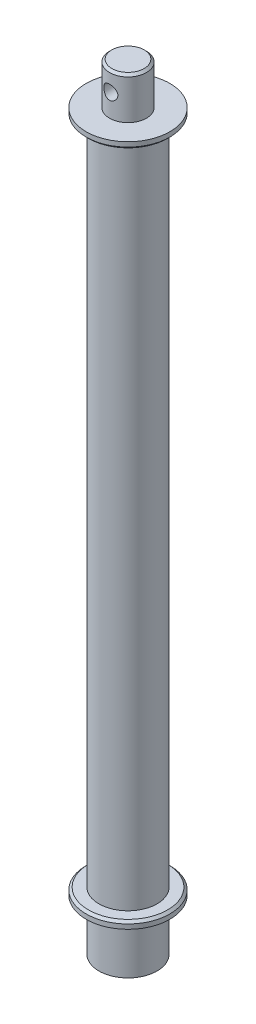
SolidWorks part; units mm, degrees
material "普通碳钢"
ref_plane "前视基准面" through (0, 0, 0) normal (0, 0, 1) x (1, 0, 0)
ref_plane "上视基准面" through (0, 0, 0) normal (0, 1, 0) x (1, 0, 0)
ref_plane "右视基准面" through (0, 0, 0) normal (1, 0, 0) x (0, 0, -1)
sketch "草图1" plane through (0, 0, 0) normal (0, 1, 0) x (1, 0, 0)
  circle A0 centre (0, 0) radius 7.95
  dimension "D1" = 15.9
extrude "凸台-拉伸1" add sketch "草图1" along normal blind 18 contours A0
sketch "草图9" plane through (0, 0, 0) normal (0, 0, 1) x (1, 0, 0)
  line L0 (0, -8.745) -> (0, 8.745) construction
  line L1 (8.745, 0) -> (-8.745, 0) construction
  circle A0 centre (0, 9.7) radius 3
  dimension "D1" = 9.7
  dimension "D2" = 6
extrude "切除-拉伸2" cut sketch "草图9" against normal through all both and the other way through all
chamfer "倒角2" distance 1 angle 45 1 edges at (0, 18, 7.95)
sketch "草图4" plane through (0, 0, 0) normal (0, 1, 0) x (1, 0, 0)
  circle A0 centre (0, 0) radius 18
extrude "凸台-拉伸2" add sketch "草图4" against normal blind 3
chamfer "倒角1" distance 1 angle 45 1 edges at (0, -3, 18)
ref_plane "基准面4" through (0, -3, 0) normal (0, -1, 0) x (-1, 0, 0)
sketch "草图5" plane through (0, -3, 0) normal (0, -1, 0) x (-1, 0, 0)
  circle A0 centre (0, 0) radius 12.5
extrude "凸台-拉伸3" add sketch "草图5" along normal blind 287.21
ref_plane "基准面5" through (0, -290.21, 0) normal (0, -1, 0) x (-1, 0, 0)
sketch "草图11" plane through (0, -290.21, 0) normal (0, -1, 0) x (-1, 0, 0)
  circle A0 centre (0, 0) radius 18
extrude "凸台-拉伸4" add sketch "草图11" along normal blind 3
chamfer "倒角3" distance 1 angle 45 1 edges at (0, -290.21, -18)
ref_plane "基准面6" through (0, -293.21, 0) normal (0, -1, 0) x (-1, 0, 0)
sketch "草图12" plane through (0, -293.21, 0) normal (0, -1, 0) x (-1, 0, 0)
  circle A0 centre (0, 0) radius 12.5
  arc A1 (1.3201, 7.2813) -> (1.0368, 7.327) centre (0, 0) ccw
  arc A2 (-0.3333, 7.3925) -> (-0.6196, 7.374) centre (0, 0) ccw
  arc A3 (-1.9699, 7.133) -> (-2.2449, 7.0513) centre (0, 0) ccw
  arc A4 (-3.5077, 6.5158) -> (-3.7577, 6.3749) centre (0, 0) ccw
  arc A5 (-4.8697, 5.5719) -> (-5.082, 5.3789) centre (0, 0) ccw
  arc A6 (-5.9875, 4.3486) -> (-6.1516, 4.1132) centre (0, 0) ccw
  arc A7 (-6.805, 2.9072) -> (-6.9126, 2.6412) centre (0, 0) ccw
  arc A8 (-7.2813, 1.3201) -> (-7.327, 1.0368) centre (0, 0) ccw
  arc A9 (-7.3925, -0.3333) -> (-7.374, -0.6196) centre (0, 0) ccw
  arc A10 (-7.133, -1.9699) -> (-7.0513, -2.2449) centre (0, 0) ccw
  arc A11 (-6.5158, -3.5077) -> (-6.3749, -3.7577) centre (0, 0) ccw
  arc A12 (-5.5719, -4.8697) -> (-5.3789, -5.082) centre (0, 0) ccw
  arc A13 (-4.3486, -5.9875) -> (-4.1132, -6.1516) centre (0, 0) ccw
  arc A14 (-2.9072, -6.805) -> (-2.6412, -6.9126) centre (0, 0) ccw
  arc A15 (-1.3201, -7.2813) -> (-1.0368, -7.327) centre (0, 0) ccw
  arc A16 (0.3333, -7.3925) -> (0.6196, -7.374) centre (0, 0) ccw
  arc A17 (1.9699, -7.133) -> (2.2449, -7.0513) centre (0, 0) ccw
  arc A18 (3.5077, -6.5158) -> (3.7577, -6.3749) centre (0, 0) ccw
  arc A19 (4.8697, -5.5719) -> (5.082, -5.3789) centre (0, 0) ccw
  arc A20 (5.9875, -4.3486) -> (6.1516, -4.1132) centre (0, 0) ccw
  arc A21 (6.805, -2.9072) -> (6.9126, -2.6412) centre (0, 0) ccw
  arc A22 (7.2813, -1.3201) -> (7.327, -1.0368) centre (0, 0) ccw
  arc A23 (7.3925, 0.3333) -> (7.374, 0.6196) centre (0, 0) ccw
  arc A24 (7.133, 1.9699) -> (7.0513, 2.2449) centre (0, 0) ccw
  arc A25 (6.5158, 3.5077) -> (6.3749, 3.7577) centre (0, 0) ccw
  arc A26 (5.5719, 4.8697) -> (5.3789, 5.082) centre (0, 0) ccw
  arc A27 (4.3486, 5.9875) -> (4.1132, 6.1516) centre (0, 0) ccw
  arc A28 (2.9072, 6.805) -> (2.6412, 6.9126) centre (0, 0) ccw
  spline S0 degree 3 poles (1.0368, 7.327) (0.9813, 7.2702) (0.9257, 7.2132) (0.8222, 7.0949) (0.7743, 7.0337) (0.6353, 6.8476) (0.5489, 6.72) (0.4775, 6.5871) knots 0 0 0 0 0.25 0.25 0.5 0.5 1 1 1 1
  spline S1 degree 3 poles (0.1466, 6.5886) (0.0874, 6.7295) (0.0225, 6.869) (-0.0958, 7.0714) (-0.1389, 7.1376) (-0.2325, 7.2668) (-0.283, 7.3297) (-0.3333, 7.3925) knots 0 0 0 0 0.5 0.5 0.75 0.75 1 1 1 1
  spline S2 degree 3 poles (-0.6196, 7.374) (-0.661, 7.3063) (-0.7026, 7.2384) (-0.7771, 7.1) (-0.81, 7.0297) (-0.9045, 6.8175) (-0.9618, 6.6745) (-1.0018, 6.5291) knots 0 0 0 0 0.25 0.25 0.5 0.5 1 1 1 1
  spline S3 degree 3 poles (-1.3247, 6.457) (-1.4136, 6.581) (-1.5073, 6.7025) (-1.6673, 6.8732) (-1.724, 6.9281) (-1.8439, 7.033) (-1.907, 7.083) (-1.9699, 7.133) knots 0 0 0 0 0.5 0.5 0.75 0.75 1 1 1 1
  spline S4 degree 3 poles (-2.2449, 7.0513) (-2.2702, 6.9761) (-2.2957, 6.9007) (-2.3374, 6.7494) (-2.3537, 6.6736) (-2.3991, 6.446) (-2.4244, 6.2939) (-2.4311, 6.1434) knots 0 0 0 0 0.25 0.25 0.5 0.5 1 1 1 1
  spline S5 degree 3 poles (-2.7298, 6.0012) (-2.8439, 6.1021) (-2.9619, 6.1997) (-3.1556, 6.3303) (-3.223, 6.3711) (-3.3629, 6.4465) (-3.4355, 6.4812) (-3.5077, 6.5158) knots 0 0 0 0 0.5 0.5 0.75 0.75 1 1 1 1
  spline S6 degree 3 poles (-3.7577, 6.3749) (-3.7657, 6.2961) (-3.7737, 6.2171) (-3.7806, 6.0606) (-3.7796, 5.9832) (-3.7736, 5.7514) (-3.7656, 5.5973) (-3.7387, 5.4493) knots 0 0 0 0 0.25 0.25 0.5 0.5 1 1 1 1
  spline S7 degree 3 poles (-3.9983, 5.2442) (-4.1317, 5.3171) (-4.2683, 5.3857) (-4.4858, 5.4696) (-4.5605, 5.4943) (-4.7134, 5.5366) (-4.7917, 5.5543) (-4.8697, 5.5719) knots 0 0 0 0 0.5 0.5 0.75 0.75 1 1 1 1
  spline S8 degree 3 poles (-5.082, 5.3789) (-5.0723, 5.3005) (-5.0626, 5.2218) (-5.0345, 5.0679) (-5.0162, 4.9928) (-4.9592, 4.7685) (-4.9181, 4.6198) (-4.8591, 4.4817) knots 0 0 0 0 0.25 0.25 0.5 0.5 1 1 1 1
  spline S9 degree 3 poles (-5.0665, 4.2239) (-5.2125, 4.2652) (-5.3608, 4.3013) (-5.5912, 4.3343) (-5.6694, 4.3418) (-5.8275, 4.349) (-5.9076, 4.3488) (-5.9875, 4.3486) knots 0 0 0 0 0.5 0.5 0.75 0.75 1 1 1 1
  spline S10 degree 3 poles (-6.1516, 4.1132) (-6.1247, 4.039) (-6.0978, 3.9646) (-6.0362, 3.8211) (-6.0017, 3.7522) (-5.8966, 3.5463) (-5.8242, 3.4102) (-5.736, 3.289) knots 0 0 0 0 0.25 0.25 0.5 0.5 1 1 1 1
  spline S11 degree 3 poles (-5.8809, 2.9915) (-6.0321, 2.9993) (-6.1847, 3.0007) (-6.4163, 2.9813) (-6.494, 2.9713) (-6.6495, 2.9432) (-6.7273, 2.9251) (-6.805, 2.9072) knots 0 0 0 0 0.5 0.5 0.75 0.75 1 1 1 1
  spline S12 degree 3 poles (-6.9126, 2.6412) (-6.87, 2.575) (-6.8273, 2.5086) (-6.7355, 2.3826) (-6.6866, 2.3232) (-6.5388, 2.1461) (-6.4383, 2.0294) (-6.3256, 1.931) knots 0 0 0 0 0.25 0.25 0.5 0.5 1 1 1 1
  spline S13 degree 3 poles (-6.4007, 1.6088) (-6.5496, 1.5827) (-6.6983, 1.5492) (-6.9194, 1.4784) (-6.9928, 1.4515) (-7.1379, 1.3897) (-7.2097, 1.3548) (-7.2813, 1.3201) knots 0 0 0 0 0.5 0.5 0.75 0.75 1 1 1 1
  spline S14 degree 3 poles (-7.327, 1.0368) (-7.2708, 0.9818) (-7.2145, 0.9267) (-7.0973, 0.8245) (-7.0365, 0.7775) (-6.8533, 0.638) (-6.7297, 0.5467) (-6.5982, 0.476) knots 0 0 0 0 0.25 0.25 0.5 0.5 1 1 1 1
  spline S15 degree 3 poles (-6.5997, 0.1451) (-6.7389, 0.0866) (-6.8759, 0.0197) (-7.0753, -0.0988) (-7.1408, -0.1413) (-7.2684, -0.2336) (-7.3305, -0.2835) (-7.3925, -0.3333) knots 0 0 0 0 0.5 0.5 0.75 0.75 1 1 1 1
  spline S16 degree 3 poles (-7.374, -0.6196) (-7.3071, -0.6606) (-7.2401, -0.7018) (-7.1033, -0.7752) (-7.0338, -0.8075) (-6.8245, -0.9025) (-6.6839, -0.9637) (-6.5402, -1.0033) knots 0 0 0 0 0.25 0.25 0.5 0.5 1 1 1 1
  spline S17 degree 3 poles (-6.468, -1.3262) (-6.5906, -1.4141) (-6.7086, -1.511) (-6.8761, -1.6712) (-6.9305, -1.727) (-7.0343, -1.8452) (-7.0837, -1.9077) (-7.133, -1.9699) knots 0 0 0 0 0.5 0.5 0.75 0.75 1 1 1 1
  spline S18 degree 3 poles (-7.0513, -2.2449) (-6.9771, -2.27) (-6.9026, -2.2952) (-6.7532, -2.3363) (-6.6783, -2.3523) (-6.4535, -2.3982) (-6.3031, -2.426) (-6.1545, -2.4326) knots 0 0 0 0 0.25 0.25 0.5 0.5 1 1 1 1
  spline S19 degree 3 poles (-6.0123, -2.7313) (-6.1121, -2.8442) (-6.2045, -2.9661) (-6.3319, -3.1598) (-6.3725, -3.2261) (-6.4474, -3.3643) (-6.4816, -3.4361) (-6.5158, -3.5077) knots 0 0 0 0 0.5 0.5 0.75 0.75 1 1 1 1
  spline S20 degree 3 poles (-6.3749, -3.7577) (-6.2971, -3.7656) (-6.219, -3.7736) (-6.0644, -3.7805) (-5.9879, -3.7795) (-5.7589, -3.774) (-5.6066, -3.7668) (-5.4604, -3.7402) knots 0 0 0 0 0.25 0.25 0.5 0.5 1 1 1 1
  spline S21 degree 3 poles (-5.2553, -3.9998) (-5.3275, -4.132) (-5.3893, -4.2723) (-5.4699, -4.4897) (-5.4948, -4.5634) (-5.5372, -4.7146) (-5.5545, -4.7923) (-5.5719, -4.8697) knots 0 0 0 0 0.5 0.5 0.75 0.75 1 1 1 1
  spline S22 degree 3 poles (-5.3789, -5.082) (-5.3014, -5.0724) (-5.2236, -5.0628) (-5.0714, -5.0353) (-4.9971, -5.0174) (-4.7754, -4.9609) (-4.6292, -4.9189) (-4.4927, -4.8606) knots 0 0 0 0 0.25 0.25 0.5 0.5 1 1 1 1
  spline S23 degree 3 poles (-4.235, -5.068) (-4.276, -5.2131) (-4.3037, -5.3642) (-4.3335, -5.5943) (-4.3416, -5.6716) (-4.3493, -5.8285) (-4.3489, -5.9081) (-4.3486, -5.9875) knots 0 0 0 0 0.5 0.5 0.75 0.75 1 1 1 1
  spline S24 degree 3 poles (-4.1132, -6.1516) (-4.0398, -6.1249) (-3.9661, -6.0982) (-3.8239, -6.0376) (-3.7554, -6.0037) (-3.5522, -5.8991) (-3.42, -5.8247) (-3.3, -5.7375) knots 0 0 0 0 0.25 0.25 0.5 0.5 1 1 1 1
  spline S25 degree 3 poles (-3.0026, -5.8824) (-3.0103, -6.0331) (-3.0024, -6.1869) (-2.9799, -6.4181) (-2.9707, -6.4953) (-2.9434, -6.6501) (-2.9252, -6.7277) (-2.9072, -6.805) knots 0 0 0 0 0.5 0.5 0.75 0.75 1 1 1 1
  spline S26 degree 3 poles (-2.6412, -6.9126) (-2.5756, -6.8703) (-2.5097, -6.8279) (-2.3845, -6.7372) (-2.3251, -6.689) (-2.1506, -6.5415) (-2.0396, -6.4388) (-1.9421, -6.3271) knots 0 0 0 0 0.25 0.25 0.5 0.5 1 1 1 1
  spline S27 degree 3 poles (-1.6199, -6.4022) (-1.5938, -6.5509) (-1.5508, -6.6993) (-1.477, -6.9199) (-1.4509, -6.9932) (-1.3899, -7.1382) (-1.3549, -7.2098) (-1.3201, -7.2813) knots 0 0 0 0 0.5 0.5 0.75 0.75 1 1 1 1
  spline S28 degree 3 poles (-1.0368, -7.327) (-0.9823, -7.2711) (-0.9275, -7.2151) (-0.8256, -7.099) (-0.7783, -7.0389) (-0.6413, -6.856) (-0.5572, -6.7303) (-0.487, -6.5997) knots 0 0 0 0 0.25 0.25 0.5 0.5 1 1 1 1
  spline S29 degree 3 poles (-0.1562, -6.6012) (-0.0976, -6.7406) (-0.0218, -6.8757) (0.0996, -7.0746) (0.1414, -7.1403) (0.2332, -7.2683) (0.2833, -7.3305) (0.3333, -7.3925) knots 0 0 0 0 0.5 0.5 0.75 0.75 1 1 1 1
  spline S30 degree 3 poles (0.6196, -7.374) (0.6604, -7.3073) (0.7013, -7.2404) (0.7751, -7.1042) (0.8079, -7.035) (0.9004, -6.8261) (0.9528, -6.6847) (0.9922, -6.5417) knots 0 0 0 0 0.25 0.25 0.5 0.5 1 1 1 1
  spline S31 degree 3 poles (1.3151, -6.4695) (1.4034, -6.5927) (1.5079, -6.7074) (1.6709, -6.8745) (1.7263, -6.9295) (1.8445, -7.034) (1.9073, -7.0836) (1.9699, -7.133) knots 0 0 0 0 0.5 0.5 0.75 0.75 1 1 1 1
  spline S32 degree 3 poles (2.2449, -7.0513) (2.2699, -6.9771) (2.2949, -6.9027) (2.3366, -6.7533) (2.3534, -6.6784) (2.3966, -6.4539) (2.4149, -6.3044) (2.4215, -6.156) knots 0 0 0 0 0.25 0.25 0.5 0.5 1 1 1 1
  spline S33 degree 3 poles (2.7202, -6.0138) (2.834, -6.1144) (2.9617, -6.2031) (3.1582, -6.33) (3.2245, -6.3713) (3.3632, -6.4471) (3.4356, -6.4815) (3.5077, -6.5158) knots 0 0 0 0 0.5 0.5 0.75 0.75 1 1 1 1
  spline S34 degree 3 poles (3.7577, -6.3749) (3.7655, -6.2969) (3.7733, -6.2187) (3.7809, -6.0635) (3.7806, -5.9867) (3.7724, -5.7579) (3.7557, -5.6082) (3.7291, -5.4619) knots 0 0 0 0 0.25 0.25 0.5 0.5 1 1 1 1
  spline S35 degree 3 poles (3.9887, -5.2568) (4.1222, -5.3297) (4.2667, -5.388) (4.4868, -5.4683) (4.5608, -5.4939) (4.7132, -5.537) (4.7916, -5.5544) (4.8697, -5.5719) knots 0 0 0 0 0.5 0.5 0.75 0.75 1 1 1 1
  spline S36 degree 3 poles (5.082, -5.3789) (5.0722, -5.301) (5.0624, -5.2229) (5.0353, -5.0696) (5.0179, -4.9946) (4.9586, -4.7732) (4.9081, -4.6312) (4.8495, -4.4942) knots 0 0 0 0 0.25 0.25 0.5 0.5 1 1 1 1
  spline S37 degree 3 poles (5.0569, -4.2365) (5.2036, -4.278) (5.3575, -4.3032) (5.5903, -4.3328) (5.6684, -4.3413) (5.8268, -4.3494) (5.9073, -4.3489) (5.9875, -4.3486) knots 0 0 0 0 0.5 0.5 0.75 0.75 1 1 1 1
  spline S38 degree 3 poles (6.1516, -4.1132) (6.1246, -4.0393) (6.0976, -3.9652) (6.0369, -3.8215) (6.0033, -3.752) (5.8957, -3.5492) (5.8142, -3.4223) (5.7265, -3.3015) knots 0 0 0 0 0.25 0.25 0.5 0.5 1 1 1 1
  spline S39 degree 3 poles (5.8714, -3.0041) (6.0238, -3.0119) (6.1796, -3.0031) (6.4136, -2.9804) (6.4917, -2.9712) (6.6483, -2.9438) (6.7268, -2.9254) (6.805, -2.9072) knots 0 0 0 0 0.5 0.5 0.75 0.75 1 1 1 1
  spline S40 degree 3 poles (6.9126, -2.6412) (6.8698, -2.5751) (6.8269, -2.5087) (6.7355, -2.3818) (6.6872, -2.3215) (6.5368, -2.1475) (6.4287, -2.042) (6.316, -1.9436) knots 0 0 0 0 0.25 0.25 0.5 0.5 1 1 1 1
  spline S41 degree 3 poles (6.3911, -1.6214) (6.5417, -1.595) (6.6919, -1.5527) (6.9154, -1.4788) (6.9896, -1.4524) (7.1364, -1.3907) (7.2089, -1.3553) (7.2813, -1.3201) knots 0 0 0 0 0.5 0.5 0.75 0.75 1 1 1 1
  spline S42 degree 3 poles (7.327, -1.0368) (7.2705, -0.9815) (7.2138, -0.9261) (7.0961, -0.8234) (7.0353, -0.7758) (6.9121, -0.6832) (6.8498, -0.6381) (6.7212, -0.5577) (6.6552, -0.5221) (6.5886, -0.4885) knots 0 0 0 0 0.25 0.25 0.5 0.5 0.75 0.75 1 1 1 1
  spline S43 degree 3 poles (6.5901, -0.1577) (6.7316, -0.0999) (6.869, -0.0256) (7.0705, 0.097) (7.1371, 0.1392) (7.2668, 0.232) (7.3297, 0.2827) (7.3925, 0.3333) knots 0 0 0 0 0.5 0.5 0.75 0.75 1 1 1 1
  spline S44 degree 3 poles (7.374, 0.6196) (7.3065, 0.661) (7.2387, 0.7025) (7.1006, 0.7767) (7.0304, 0.8093) (6.8189, 0.9046) (6.6764, 0.9634) (6.5306, 0.9907) knots 0 0 0 0 0.25 0.25 0.5 0.5 1 1 1 1
  spline S45 degree 3 poles (6.4585, 1.3136) (6.583, 1.403) (6.7015, 1.5041) (6.8717, 1.6671) (6.9271, 1.7234) (7.0327, 1.8432) (7.0829, 1.9067) (7.133, 1.9699) knots 0 0 0 0 0.5 0.5 0.75 0.75 1 1 1 1
  spline S46 degree 3 poles (7.0513, 2.2449) (6.9761, 2.2701) (6.9008, 2.2954) (6.7495, 2.3377) (6.6737, 2.3548) (6.4464, 2.3973) (6.2952, 2.4133) (6.1449, 2.42) knots 0 0 0 0 0.25 0.25 0.5 0.5 1 1 1 1
  spline S47 degree 3 poles (6.0027, 2.7188) (6.1043, 2.8336) (6.1983, 2.9576) (6.3284, 3.154) (6.3699, 3.2214) (6.4462, 3.3619) (6.481, 3.4349) (6.5158, 3.5077) knots 0 0 0 0 0.5 0.5 0.75 0.75 1 1 1 1
  spline S48 degree 3 poles (6.3749, 3.7577) (6.296, 3.7655) (6.2168, 3.7735) (6.0597, 3.781) (5.9819, 3.7807) (5.7505, 3.7717) (5.599, 3.7546) (5.4508, 3.7276) knots 0 0 0 0 0.25 0.25 0.5 0.5 1 1 1 1
  spline S49 degree 3 poles (5.2457, 3.9872) (5.3192, 4.1218) (5.3845, 4.2628) (5.468, 4.483) (5.4934, 4.558) (5.5364, 4.712) (5.5542, 4.791) (5.5719, 4.8697) knots 0 0 0 0 0.5 0.5 0.75 0.75 1 1 1 1
  spline S50 degree 3 poles (5.3789, 5.082) (5.3001, 5.0721) (5.2211, 5.0622) (5.0662, 5.0345) (4.9904, 5.0168) (4.7664, 4.9568) (4.6218, 4.9073) (4.4832, 4.848) knots 0 0 0 0 0.25 0.25 0.5 0.5 1 1 1 1
  spline S51 degree 3 poles (4.2254, 5.0554) (4.2671, 5.203) (4.3006, 5.3543) (4.3336, 5.5873) (4.3415, 5.6661) (4.3491, 5.8258) (4.3488, 5.9068) (4.3486, 5.9875) knots 0 0 0 0 0.5 0.5 0.75 0.75 1 1 1 1
  spline S52 degree 3 poles (4.1132, 6.1516) (4.0385, 6.1243) (3.9636, 6.0971) (3.8187, 6.0355) (3.7489, 6.0013) (3.5435, 5.8932) (3.4125, 5.8137) (3.2905, 5.725) knots 0 0 0 0 0.25 0.25 0.5 0.5 1 1 1 1
  spline S53 degree 3 poles (2.993, 5.8699) (3.0009, 6.0229) (3.001, 6.1775) (2.9817, 6.4118) (2.9718, 6.4903) (2.9436, 6.6476) (2.9253, 6.7264) (2.9072, 6.805) knots 0 0 0 0 0.5 0.5 0.75 0.75 1 1 1 1
  spline S54 degree 3 poles (2.6412, 6.9126) (2.5745, 6.8695) (2.5075, 6.8263) (2.38, 6.7339) (2.3196, 6.6849) (2.143, 6.534) (2.0318, 6.4282) (1.9325, 6.3145) knots 0 0 0 0 0.25 0.25 0.5 0.5 1 1 1 1
  spline S55 degree 3 poles (1.6103, 6.3896) (1.5839, 6.5404) (1.5508, 6.691) (1.4802, 6.9149) (1.453, 6.9892) (1.3905, 7.1361) (1.3552, 7.2088) (1.3201, 7.2813) knots 0 0 0 0 0.5 0.5 0.75 0.75 1 1 1 1
  spline S56 degree 3 poles (0.4775, 6.5871) (0.4657, 6.56) (0.447, 6.5346) (0.3926, 6.4942) (0.3549, 6.4794) (0.2744, 6.4783) (0.2342, 6.4929) (0.1775, 6.5346) (0.1584, 6.5609) (0.1466, 6.5886) knots 0 0 0 0 0.25 0.25 0.5 0.5 0.75 0.75 1 1 1 1
  spline S57 degree 3 poles (-1.0018, 6.5291) (-1.0073, 6.5001) (-1.0199, 6.4712) (-1.0639, 6.4196) (-1.0973, 6.3968) (-1.1756, 6.3779) (-1.218, 6.3832) (-1.2826, 6.4111) (-1.3071, 6.4326) (-1.3247, 6.457) knots 0 0 0 0 0.25 0.25 0.5 0.5 0.75 0.75 1 1 1 1
  spline S58 degree 3 poles (-2.4311, 6.1434) (-2.4299, 6.1139) (-2.4358, 6.0829) (-2.4672, 6.0228) (-2.4947, 5.9931) (-2.5668, 5.9573) (-2.6094, 5.953) (-2.6785, 5.9659) (-2.7072, 5.9813) (-2.7298, 6.0012) knots 0 0 0 0 0.25 0.25 0.5 0.5 0.75 0.75 1 1 1 1
  spline S59 degree 3 poles (-3.7387, 5.4493) (-3.731, 5.4208) (-3.7298, 5.3893) (-3.7471, 5.3237) (-3.7673, 5.2887) (-3.8296, 5.2377) (-3.8702, 5.224) (-3.9404, 5.2212) (-3.9718, 5.2299) (-3.9983, 5.2442) knots 0 0 0 0 0.25 0.25 0.5 0.5 0.75 0.75 1 1 1 1
  spline S60 degree 3 poles (-4.8591, 4.4817) (-4.8452, 4.4555) (-4.837, 4.4251) (-4.8393, 4.3573) (-4.8512, 4.3187) (-4.9006, 4.2551) (-4.9371, 4.2327) (-5.005, 4.2144) (-5.0375, 4.2158) (-5.0665, 4.2239) knots 0 0 0 0 0.25 0.25 0.5 0.5 0.75 0.75 1 1 1 1
  spline S61 degree 3 poles (-5.736, 3.289) (-5.7167, 3.2666) (-5.7019, 3.2387) (-5.6891, 3.1722) (-5.6921, 3.1318) (-5.7261, 3.0588) (-5.7567, 3.0289) (-5.8188, 2.9959) (-5.8508, 2.9901) (-5.8809, 2.9915) knots 0 0 0 0 0.25 0.25 0.5 0.5 0.75 0.75 1 1 1 1
  spline S62 degree 3 poles (-6.3256, 1.931) (-6.3017, 1.9135) (-6.2812, 1.8896) (-6.2538, 1.8276) (-6.2478, 1.7876) (-6.2647, 1.7088) (-6.2879, 1.6729) (-6.3411, 1.6269) (-6.371, 1.6141) (-6.4007, 1.6088) knots 0 0 0 0 0.25 0.25 0.5 0.5 0.75 0.75 1 1 1 1
  spline S63 degree 3 poles (-6.5982, 0.476) (-6.5716, 0.4636) (-6.5469, 0.4446) (-6.5075, 0.3902) (-6.4933, 0.3528) (-6.4923, 0.2735) (-6.5062, 0.2338) (-6.5468, 0.1769) (-6.5725, 0.1574) (-6.5997, 0.1451) knots 0 0 0 0 0.25 0.25 0.5 0.5 0.75 0.75 1 1 1 1
  spline S64 degree 3 poles (-6.5402, -1.0033) (-6.5113, -1.0091) (-6.4827, -1.0219) (-6.4318, -1.0661) (-6.4093, -1.0994) (-6.3905, -1.1771) (-6.3955, -1.2192) (-6.4229, -1.2837) (-6.444, -1.3083) (-6.468, -1.3262) knots 0 0 0 0 0.25 0.25 0.5 0.5 0.75 0.75 1 1 1 1
  spline S65 degree 3 poles (-6.1545, -2.4326) (-6.125, -2.4315) (-6.0941, -2.4375) (-6.0342, -2.469) (-6.0046, -2.4965) (-5.9688, -2.5684) (-5.9645, -2.6109) (-5.9772, -2.68) (-5.9925, -2.7087) (-6.0123, -2.7313) knots 0 0 0 0 0.25 0.25 0.5 0.5 0.75 0.75 1 1 1 1
  spline S66 degree 3 poles (-5.4604, -3.7402) (-5.4318, -3.7324) (-5.4003, -3.7312) (-5.3347, -3.7484) (-5.2996, -3.7686) (-5.2485, -3.831) (-5.2349, -3.8716) (-5.2321, -3.9419) (-5.2409, -3.9733) (-5.2553, -3.9998) knots 0 0 0 0 0.25 0.25 0.5 0.5 0.75 0.75 1 1 1 1
  spline S67 degree 3 poles (-4.4927, -4.8606) (-4.4666, -4.8465) (-4.4362, -4.8382) (-4.3683, -4.8403) (-4.3295, -4.8522) (-4.2657, -4.9017) (-4.2434, -4.9383) (-4.2252, -5.0064) (-4.2268, -5.039) (-4.235, -5.068) knots 0 0 0 0 0.25 0.25 0.5 0.5 0.75 0.75 1 1 1 1
  spline S68 degree 3 poles (-3.3, -5.7375) (-3.2777, -5.7181) (-3.2498, -5.7032) (-3.1832, -5.6902) (-3.1428, -5.6931) (-3.0696, -5.7272) (-3.0397, -5.7579) (-3.0067, -5.8202) (-3.001, -5.8523) (-3.0026, -5.8824) knots 0 0 0 0 0.25 0.25 0.5 0.5 0.75 0.75 1 1 1 1
  spline S69 degree 3 poles (-1.9421, -6.3271) (-1.9246, -6.3033) (-1.9007, -6.2827) (-1.8387, -6.2554) (-1.7987, -6.2493) (-1.72, -6.2662) (-1.684, -6.2893) (-1.638, -6.3426) (-1.6252, -6.3725) (-1.6199, -6.4022) knots 0 0 0 0 0.25 0.25 0.5 0.5 0.75 0.75 1 1 1 1
  spline S70 degree 3 poles (-0.487, -6.5997) (-0.4751, -6.5727) (-0.4563, -6.5476) (-0.4019, -6.5074) (-0.3644, -6.4928) (-0.2843, -6.4917) (-0.2441, -6.5061) (-0.1873, -6.5474) (-0.1681, -6.5736) (-0.1562, -6.6012) knots 0 0 0 0 0.25 0.25 0.5 0.5 0.75 0.75 1 1 1 1
  spline S71 degree 3 poles (0.9922, -6.5417) (0.9977, -6.5126) (1.0103, -6.4837) (1.0543, -6.4322) (1.0876, -6.4094) (1.1659, -6.3904) (1.2084, -6.3957) (1.273, -6.4237) (1.2975, -6.4451) (1.3151, -6.4695) knots 0 0 0 0 0.25 0.25 0.5 0.5 0.75 0.75 1 1 1 1
  spline S72 degree 3 poles (2.4215, -6.156) (2.4204, -6.1264) (2.4261, -6.0958) (2.4577, -6.0353) (2.4851, -6.0057) (2.5574, -5.9698) (2.5995, -5.9655) (2.669, -5.9784) (2.6976, -5.9939) (2.7202, -6.0138) knots 0 0 0 0 0.25 0.25 0.5 0.5 0.75 0.75 1 1 1 1
  spline S73 degree 3 poles (3.7291, -5.4619) (3.7214, -5.4333) (3.7202, -5.4018) (3.7375, -5.3364) (3.7577, -5.3013) (3.82, -5.2503) (3.8605, -5.2366) (3.9308, -5.2337) (3.9622, -5.2424) (3.9887, -5.2568) knots 0 0 0 0 0.25 0.25 0.5 0.5 0.75 0.75 1 1 1 1
  spline S74 degree 3 poles (4.8495, -4.4942) (4.8356, -4.4681) (4.8274, -4.4378) (4.8298, -4.3696) (4.8414, -4.3315) (4.8916, -4.267) (4.9276, -4.2453) (4.9954, -4.2269) (5.028, -4.2284) (5.0569, -4.2365) knots 0 0 0 0 0.25 0.25 0.5 0.5 0.75 0.75 1 1 1 1
  spline S75 degree 3 poles (5.7265, -3.3015) (5.7071, -3.2791) (5.6924, -3.2513) (5.6795, -3.1848) (5.6826, -3.1442) (5.7167, -3.0712) (5.7469, -3.0416) (5.8094, -3.0084) (5.8413, -3.0027) (5.8714, -3.0041) knots 0 0 0 0 0.25 0.25 0.5 0.5 0.75 0.75 1 1 1 1
  spline S76 degree 3 poles (6.316, -1.9436) (6.2922, -1.9261) (6.2717, -1.9022) (6.2443, -1.8403) (6.2382, -1.8001) (6.2552, -1.7213) (6.2781, -1.6856) (6.3316, -1.6393) (6.3615, -1.6267) (6.3911, -1.6214) knots 0 0 0 0 0.25 0.25 0.5 0.5 0.75 0.75 1 1 1 1
  spline S77 degree 3 poles (6.5886, -0.4885) (6.5615, -0.4767) (6.5362, -0.458) (6.4957, -0.4037) (6.4809, -0.3663) (6.4798, -0.2851) (6.4942, -0.2456) (6.5362, -0.1883) (6.5624, -0.1694) (6.5901, -0.1577) knots 0 0 0 0 0.25 0.25 0.5 0.5 0.75 0.75 1 1 1 1
  spline S78 degree 3 poles (6.5306, 0.9907) (6.5015, 0.9962) (6.4726, 1.0088) (6.4211, 1.0529) (6.3983, 1.0863) (6.3794, 1.1647) (6.3845, 1.2065) (6.4127, 1.2718) (6.4341, 1.296) (6.4585, 1.3136) knots 0 0 0 0 0.25 0.25 0.5 0.5 0.75 0.75 1 1 1 1
  spline S79 degree 3 poles (6.1449, 2.42) (6.1154, 2.4189) (6.0844, 2.4247) (6.0244, 2.4562) (5.9947, 2.4836) (5.9588, 2.5558) (5.9545, 2.5983) (5.9674, 2.6675) (5.9828, 2.6961) (6.0027, 2.7188) knots 0 0 0 0 0.25 0.25 0.5 0.5 0.75 0.75 1 1 1 1
  spline S80 degree 3 poles (5.4508, 3.7276) (5.4223, 3.7199) (5.3908, 3.7187) (5.3253, 3.736) (5.2902, 3.7562) (5.2392, 3.8185) (5.2255, 3.8589) (5.2227, 3.9296) (5.2314, 3.9607) (5.2457, 3.9872) knots 0 0 0 0 0.25 0.25 0.5 0.5 0.75 0.75 1 1 1 1
  spline S81 degree 3 poles (4.4832, 4.848) (4.4571, 4.8341) (4.4267, 4.826) (4.359, 4.8282) (4.3204, 4.8401) (4.2568, 4.8893) (4.2344, 4.9258) (4.2159, 4.9937) (4.2173, 5.0264) (4.2254, 5.0554) knots 0 0 0 0 0.25 0.25 0.5 0.5 0.75 0.75 1 1 1 1
  spline S82 degree 3 poles (3.2905, 5.725) (3.2681, 5.7056) (3.2402, 5.6909) (3.1737, 5.678) (3.1334, 5.681) (3.0604, 5.715) (3.0304, 5.7456) (2.9974, 5.8077) (2.9916, 5.8398) (2.993, 5.8699) knots 0 0 0 0 0.25 0.25 0.5 0.5 0.75 0.75 1 1 1 1
  spline S83 degree 3 poles (1.9325, 6.3145) (1.915, 6.2907) (1.8911, 6.2701) (1.8291, 6.2428) (1.7891, 6.2367) (1.7104, 6.2536) (1.6744, 6.2768) (1.6284, 6.33) (1.6156, 6.36) (1.6103, 6.3896) knots 0 0 0 0 0.25 0.25 0.5 0.5 0.75 0.75 1 1 1 1
extrude "凸台-拉伸5" add sketch "草图12" along normal blind 22
